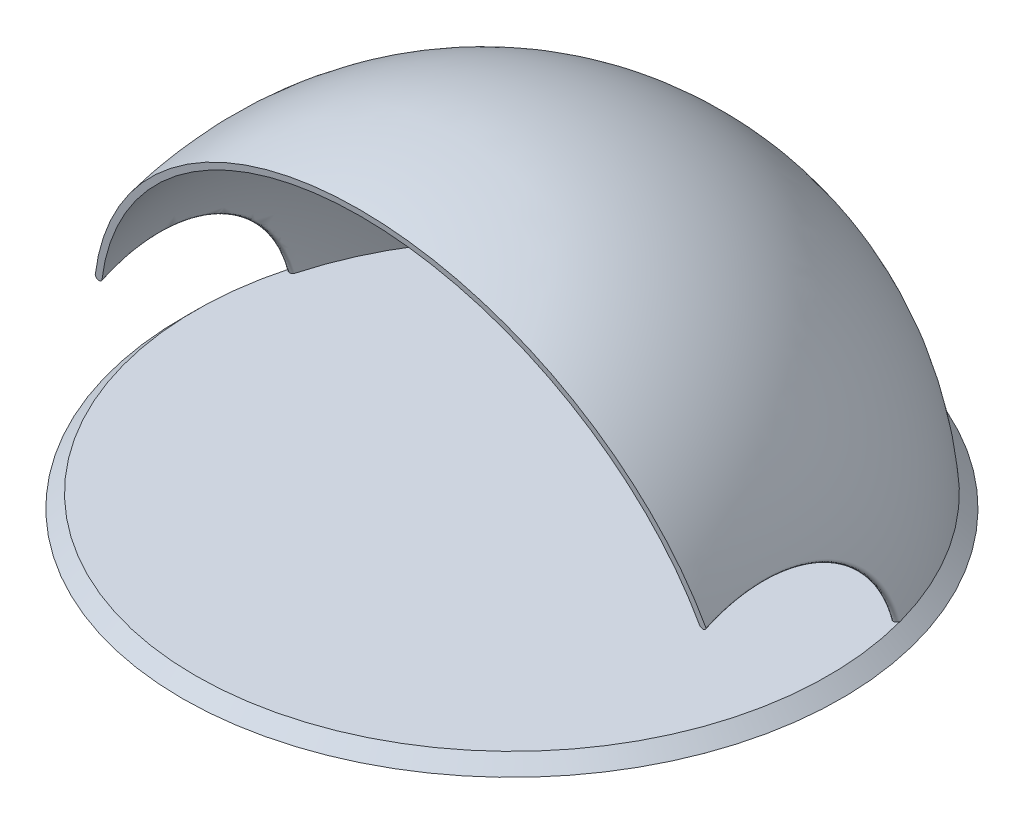
SolidWorks part; units mm, degrees
ref_plane "Front Plane" through (0, 0, 0) normal (0, 0, 1) x (1, 0, 0)
ref_plane "Top Plane" through (0, 0, 0) normal (0, 1, 0) x (1, 0, 0)
ref_plane "Right Plane" through (0, 0, 0) normal (1, 0, 0) x (0, 0, -1)
sketch "Sketch1" plane through (0, 0, 0) normal (0, 1, 0) x (1, 0, 0)
  circle A0 centre (0, 0) radius 500
  dimension "D1" = 1000
extrude "Boss-Extrude1" add sketch "Sketch1" along normal blind 20 draft 45
sketch "Sketch2" plane through (0, 20, 0) normal (0, 1, 0) x (1, 0, 0)
  arc A0 (-462.8942, 127) -> (462.8942, 127) centre (0, 0) cw
  circle A1 centre (0, 0) radius 480 construction
  arc A2 (-453.2505, 124.3542) -> (453.2505, 124.3542) centre (0, 0) cw
  arc A3 (-462.8942, 127) -> (-453.2505, 124.3542) centre (-458.0723, 125.6771) ccw
  arc A4 (462.8942, 127) -> (453.2505, 124.3542) centre (458.0723, 125.6771) cw
  point P6 (0, 0)
  point P7 (-446.9777, 174.9598)
  dimension "D1" = 127
  dimension "D2" = 10
sketch "Sketch3" plane through (0, 0, 0) normal (1, 0, 0) x (0, 0, -1)
  arc A0 (480, 20) -> (-231.0263, 508) centre (-79.944, -33.86) ccw
  dimension "D1" = 508
sweep "Sweep1" add profiles "Sketch2" path "Sketch3"
